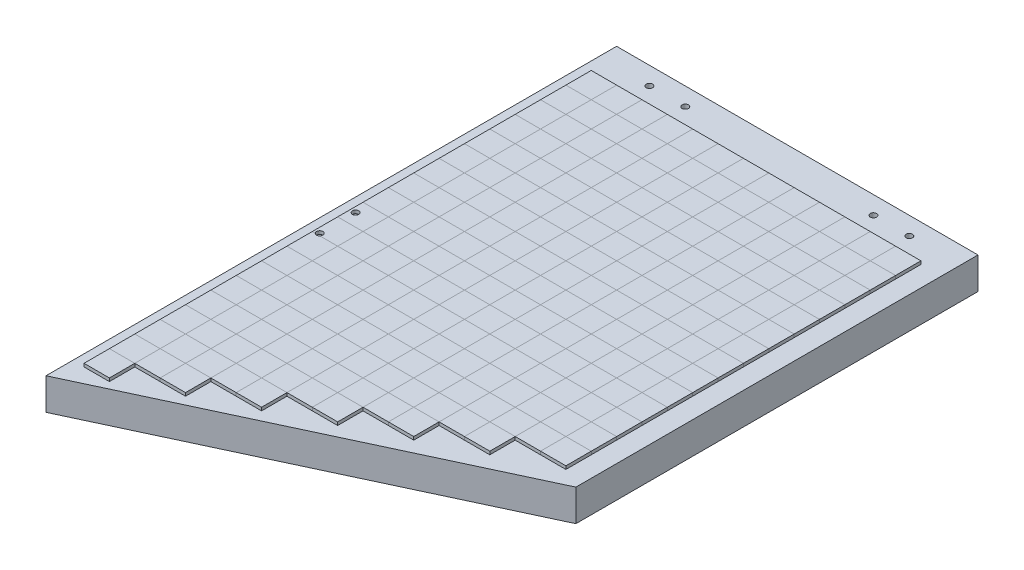
SolidWorks part; units mm, degrees
material "Silicon"
ref_plane "Front Plane" through (0, 0, 0) normal (0, 0, 1) x (1, 0, 0)
ref_plane "Top Plane" through (0, 0, 0) normal (0, 1, 0) x (1, 0, 0)
ref_plane "Right Plane" through (0, 0, 0) normal (1, 0, 0) x (0, 0, -1)
sketch "Sketch1" plane through (0, 0, 0) normal (0, 1, 0) x (1, 0, 0)
  line L0 (-349.5, 0) -> (374.4, 0)
  line L1 (-349.5, 0) -> (-349.5, -1143)
  line L2 (-349.5, -1143) -> (374.4, -805.4399)
  line L3 (374.4, 0) -> (374.4, -805.4399)
  dimension "D1" = 723.9
  dimension "D2" = 1143
  dimension "D3" = 65
extrude "Boss-Extrude1" add sketch "Sketch1" along normal blind 63.5
ref_plane "Plane1" through (0, 66.04, 0) normal (0, 1, 0) x (1, 0, 0)
sketch "Sketch6" plane through (0, 66.04, 0) normal (0, 1, 0) x (1, 0, 0)
  line L0 (-349.5, 0) -> (374.4, 0) construction
  line L1 (12.45, 0) -> (12.45, -195.869) construction
  line L2 (-349.5, 0) -> (-349.5, -1143) construction
  line L3 (374.4, -805.4399) -> (374.4, 0) construction
  circle A0 centre (-247.9, -35.941) radius 6.35
  circle A1 centre (-176.018, -35.941) radius 6.35
  circle A2 centre (200.918, -35.941) radius 6.35
  circle A3 centre (272.8, -35.941) radius 6.35
  dimension "D1" = 12.7
  dimension "D2" = 101.6
  dimension "D3" = 173.482
  dimension "D4" = 173.482
  dimension "D5" = 101.6
  dimension "D6" = 35.941
  dimension "D7" = 35.941
  dimension "D8" = 35.941
  dimension "D9" = 35.941
ref_plane "Plane2" through (0, 66.04, 0) normal (0, 1, 0) x (1, 0, 0)
sketch "Sketch8" plane through (0, 66.04, 0) normal (0, 1, 0) x (1, 0, 0)
  line L0 (-349.5, 0) -> (-349.5, -1143) construction
  line L1 (-273.3, -76.2) -> (-324.1, -76.2)
  line L2 (-273.3, -76.2) -> (-273.3, -127)
  line L3 (-273.3, -127) -> (-324.1, -127)
  line L4 (-324.1, -76.2) -> (-324.1, -127)
  line L5 (-273.3, -76.2) -> (-324.1, -127) construction
  line L6 (-273.3, -127) -> (-324.1, -76.2) construction
  line L7 (-349.5, 0) -> (374.4, 0) construction
  point P0 (-298.7, -101.6)
  dimension "D1" = 50.8
  dimension "D2" = 50.8
  dimension "D3" = 25.4
  dimension "D4" = 76.2
extrude "Boss-Extrude2" add sketch "Sketch8" along normal blind 6.35 separate body
pattern_linear "LPattern1" count 13 spacing 50.8 along (1, 0, 0) count 20 spacing 50.8 along (0, 0, 1) of "Boss-Extrude2"
ref_plane "Plane3" through (0, 72.39, 0) normal (0, 1, 0) x (1, 0, 0)
sketch "Sketch10" plane through (0, 72.39, 0) normal (0, 1, 0) x (1, 0, 0)
  line L0 (-349.5, -1143) -> (374.4, -805.4399)
  line L1 (-349.5, -1143) -> (374.4, -805.4399) construction
  line L2 (-349.5, 0) -> (-349.5, -1143) construction
  line L3 (374.4, -805.4399) -> (374.4, -1218.7471)
  line L4 (374.4, -1218.7471) -> (-349.5, -1218.7471)
  line L5 (-349.5, -1218.7471) -> (-349.5, -1143)
extrude "Cut-Extrude1" cut sketch "Sketch10" against normal through all
sketch "Sketch12" plane through (0, 72.39, 0) normal (0, 1, 0) x (1, 0, 0)
  line L0 (-273.3, -1092.2) -> (-273.3, -1041.4)
  line L1 (-273.3, -1041.4) -> (-171.7, -1041.4)
  line L2 (-171.7, -1041.4) -> (-171.7, -990.6)
  line L3 (-171.7, -990.6) -> (-70.1, -990.6)
  line L4 (-70.1, -990.6) -> (-70.1, -939.8)
  line L5 (-70.1, -939.8) -> (31.5, -939.8)
  line L6 (31.5, -939.8) -> (31.5, -889)
  line L7 (31.5, -889) -> (133.1, -889)
  line L8 (133.1, -889) -> (133.1, -838.2)
  line L9 (133.1, -838.2) -> (234.7, -838.2)
  line L10 (234.7, -838.2) -> (234.7, -787.4)
  line L11 (234.7, -787.4) -> (336.3, -787.4)
  line L12 (336.3, -787.4) -> (336.3, -1181.897)
  line L13 (336.3, -1181.897) -> (-273.3, -1181.897)
  line L14 (-273.3, -1181.897) -> (-273.3, -1092.2)
extrude "Cut-Extrude3" cut sketch "Sketch12" against normal blind 6.35
sketch "Sketch13" plane through (0, 72.39, 0) normal (0, 1, 0) x (1, 0, 0)
  line L2 (-349.5, 0) -> (-349.5, -1143) construction
  line L4 (-349.5, 0) -> (374.4, 0) construction
  circle A0 centre (-313.559, -558.8) radius 6.35
  circle A1 centre (-313.559, -630.682) radius 6.35
  dimension "D1" = 12.7
  dimension "D4" = 12.7
  dimension "D2" = 35.941
  dimension "D3" = 558.8
  dimension "D5" = 71.882
  dimension "D6" = 35.941
extrude "Cut-Extrude4" cut sketch "Sketch13" against normal through all
extrude "Cut-Extrude5" cut sketch "Sketch6" against normal through all
sketch "Sketch14" plane through (0, 72.39, 0) normal (0, 1, 0) x (1, 0, 0)
  line L0 (-313.559, -558.8) -> (-363.8743, -558.8) construction
  line L1 (-363.8743, -558.8) -> (-363.8743, -1143) construction
  line L2 (-349.5, -1143) -> (-376.3788, -1143) construction
  dimension "D1" = 584.2
